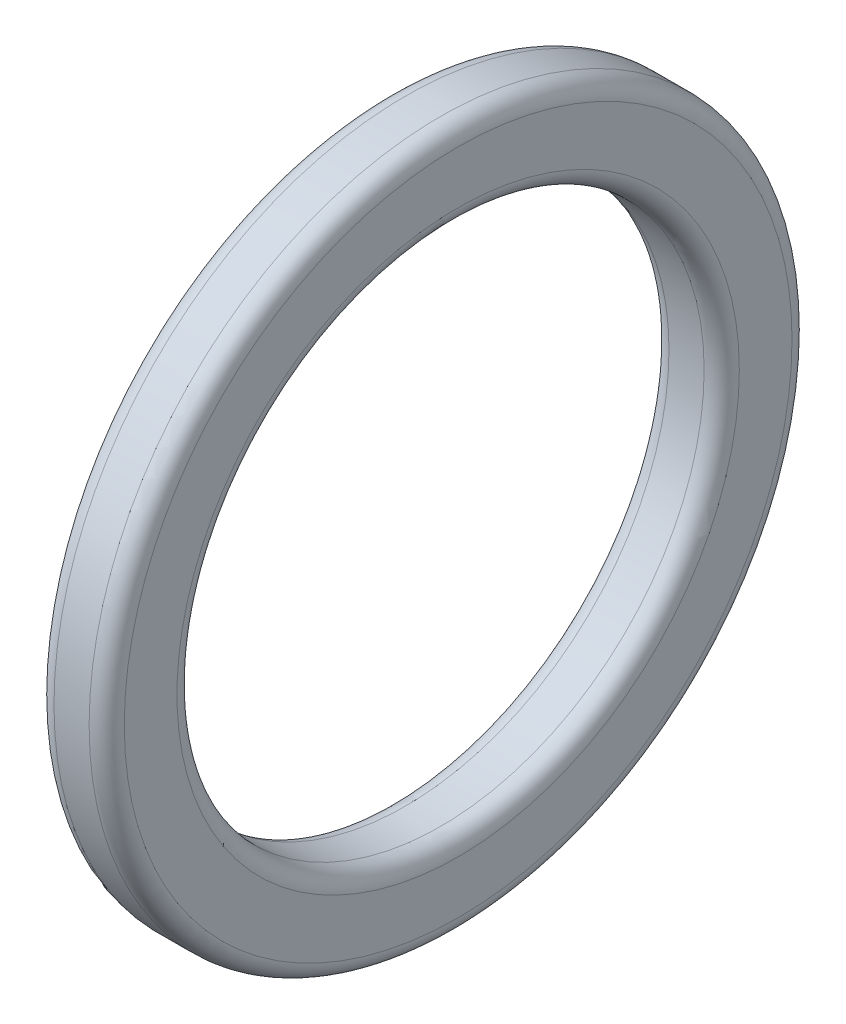
SolidWorks part; units mm, degrees
ref_plane "Plan1" through (0, 0, 0) normal (0, 0, 1) x (1, 0, 0)
ref_plane "Plan2" through (0, 0, 0) normal (0, 1, 0) x (1, 0, 0)
ref_plane "Plan3" through (0, 0, 0) normal (1, 0, 0) x (0, 0, -1)
sketch "Esquisse1" plane through (0, 0, 0) normal (0, 0, 1) x (1, 0, 0)
  line L0 (0, 0) -> (-20, 0) construction
  line L1 (0, 15) -> (4, 15)
  line L2 (0, 15) -> (0, 20)
  line L3 (0, 20) -> (4, 20)
  line L4 (4, 15) -> (4, 20)
  dimension "D1" = 20
  dimension "D2" = 15
  dimension "D3" = 4
revolve "Base-Révolution" add sketch "Esquisse1" angle 360 about L0
fillet "Congé1" radius 1
